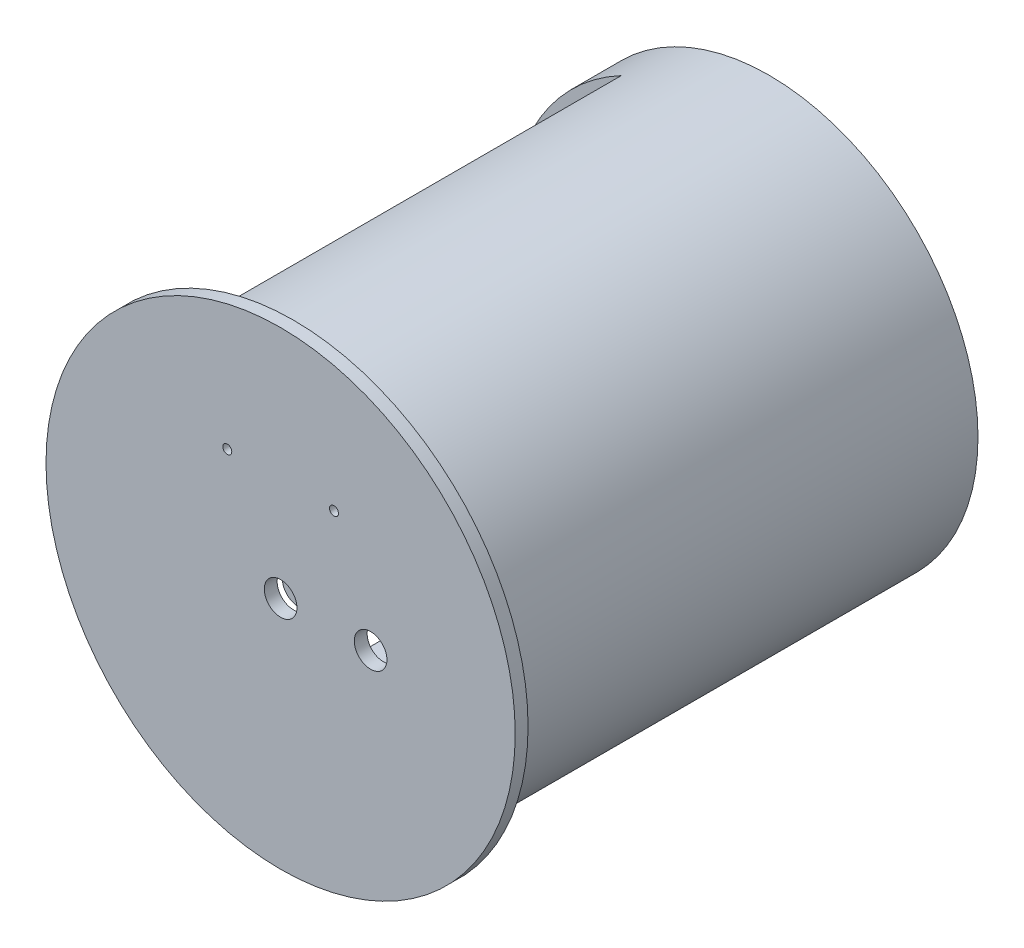
SolidWorks part; units mm, degrees
ref_plane "Alzado" through (0, 0, 0) normal (0, 0, 1) x (1, 0, 0)
ref_plane "Planta" through (0, 0, 0) normal (0, 1, 0) x (1, 0, 0)
ref_plane "Vista lateral" through (0, 0, 0) normal (1, 0, 0) x (0, 0, -1)
sketch "Croquis1" plane through (0, 0, 0) normal (0, 0, 1) x (1, 0, 0)
  circle A0 centre (0, 0) radius 162.5
extrude "Saliente-Extruir1" add sketch "Croquis1" along normal blind 370
ref_plane "Plano1" through (0, 0, 15) normal (0, 0, 1) x (1, 0, 0)
sketch "Croquis2" plane through (0, 0, 15) normal (0, 0, 1) x (1, 0, 0)
  circle A0 centre (0, 0) radius 132
extrude "Cortar-Extruir1" cut sketch "Croquis2" along normal blind 417
sketch "Croquis3" plane through (0, 0, 0) normal (1, 0, 0) x (0, 0, -1)
  line L0 (-370, -162.5) -> (-15, -162.5) construction
  line L1 (-15, 178.75) -> (-15, -178.75) construction
  line L2 (-370, -162.5) -> (0, -162.5) construction
  line L4 (-38.7674, 143.5323) -> (-346.2326, 143.5323)
  line L5 (-38.7674, 143.5323) -> (-38.7674, -143.5323)
  line L6 (-38.7674, -143.5323) -> (-346.2326, -143.5323)
  line L7 (-346.2326, 143.5323) -> (-346.2326, -143.5323)
  line L8 (-38.7674, 143.5323) -> (-346.2326, -143.5323) construction
  line L9 (-38.7674, -143.5323) -> (-346.2326, 143.5323) construction
  point P7 (-192.5, 0)
extrude "Cortar-Extruir2" cut sketch "Croquis3" against normal blind 417
ref_plane "Plano2" through (0, 0, 370) normal (0, 0, 1) x (1, 0, 0)
sketch "Croquis4" plane through (0, 0, 370) normal (0, 0, 1) x (1, 0, 0)
  circle A0 centre (0, 0) radius 182.5
  circle A1 centre (0, 0) radius 12.7
  circle A2 centre (70, 0) radius 12.7
  circle A3 centre (-41.5, 79.7728) radius 3.5
  circle A4 centre (41.5, 79.7728) radius 3.5
extrude "Saliente-Extruir2" add sketch "Croquis4" along normal blind 10
sketch "Croquis5" plane through (0, 0, 0) normal (1, 0, 0) x (0, 0, -1)
  line L1 (-155.3282, 42.685) -> (-31.5854, 42.685)
  line L2 (-195.3282, 2.685) -> (-195.3282, -2.685)
  line L3 (-155.3282, -42.685) -> (-31.5854, -42.685)
  line L4 (-31.5854, 42.685) -> (-31.5854, -42.685)
  arc A0 (-195.3282, -2.685) -> (-155.3282, -42.685) centre (-155.3282, -2.685) ccw
  arc A1 (-195.3282, 2.685) -> (-155.3282, 42.685) centre (-155.3282, 2.685) cw
  point P0 (-113.4568, 0)
extrude "Saliente-Extruir3" add sketch "Croquis5" against normal blind 84 separate body
sketch "Croquis6" plane through (0, 0, 0) normal (1, 0, 0) x (0, 0, -1)
  circle A0 centre (-140.989, 9.4416) radius 11.0394
  circle A1 centre (-110.9532, -16.5724) radius 15.2732
  circle A2 centre (-99.615, 26.7697) radius 8.1857
extrude "Saliente-Extruir4" add sketch "Croquis6" against normal blind 113
sketch "Croquis7" plane through (0, 0, 15) normal (0, 0, 1) x (1, 0, 0)
  circle A0 centre (0, 0) radius 12.7
extrude "Saliente-Extruir5" add sketch "Croquis7" along normal blind 351
